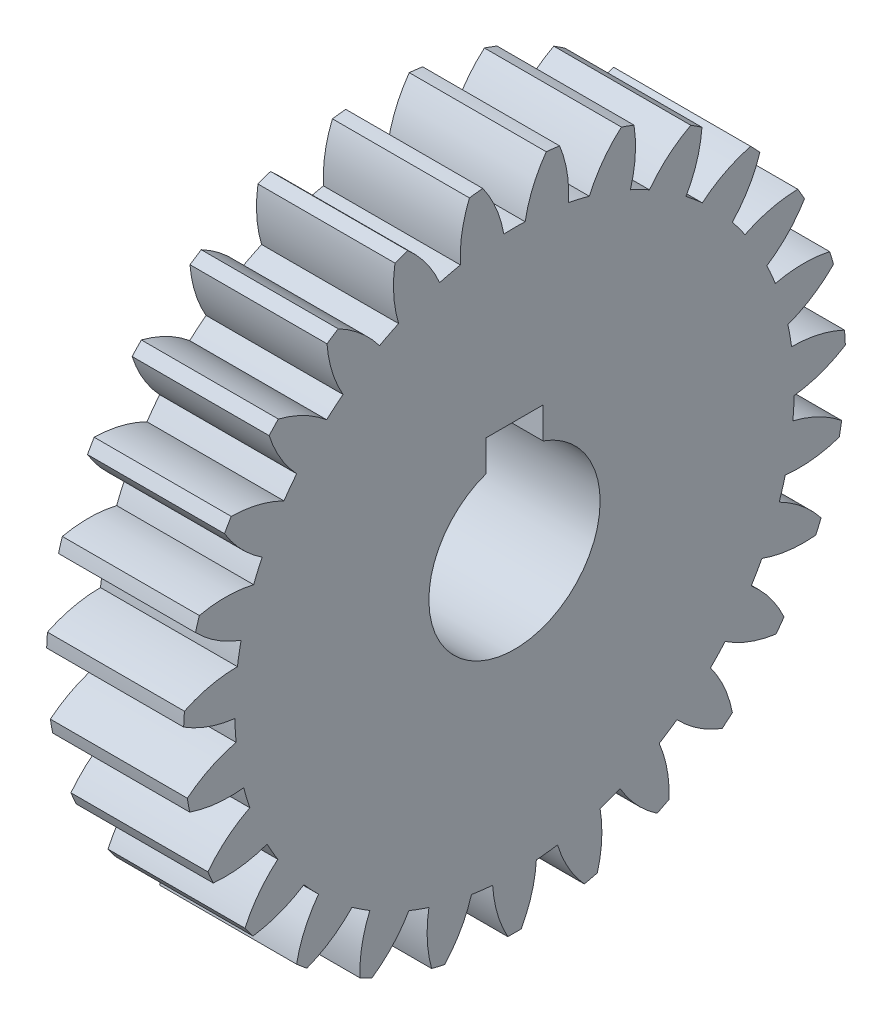
SolidWorks part; units mm, degrees
ref_plane "Plane1" through (0, 0, 0) normal (0, 0, 1) x (1, 0, 0)
ref_plane "Plane2" through (0, 0, 0) normal (0, 1, 0) x (1, 0, 0)
ref_plane "Plane3" through (0, 0, 0) normal (1, 0, 0) x (0, 0, -1)
sketch "HoldingSke" plane through (0, 0, 0) normal (0, 1, 0) x (1, 0, 0)
  line L0 (0, 0) -> (0.4455, -0.227)
  line L1 (-15, 0) -> (100, 0) construction
  line L2 (0, 0) -> (-2.1039, 2.3779)
  line L3 (0, 0) -> (-11.863, 4.5341)
  line L4 (0, 0) -> (7.6947, 3.9207)
  line L5 (0, 0) -> (-46.8476, -17.4728)
  line L6 (0, 0) -> (-9.9476, -6.7116)
  line L7 (-2.1039, 2.3779) -> (8.6586, 51.2059)
  line L8 (-76.2, 54.61) -> (-73.9, 54.61)
  line L9 (-71.009, 38.7566) -> (-53.1078, 45.2721)
  line L10 (-76.2, 71.12) -> (104.1128, 71.12)
  line L11 (0, 0) -> (-12, 0)
  line L12 (-76.2, 101.6) -> (-76.133, 101.6)
  line L13 (24.9733, 27.94) -> (52.9518, 28.4284)
  line L14 (24.9733, 27.94) -> (24.9743, 27.94)
  line L15 (24.9733, 27.94) -> (100.4006, 29.5858)
  line L16 (-63.627, -2) -> (-12.827, -2)
  circle A0 centre (0, 0) radius 7.5
  circle A1 centre (0, 0) radius 24.499
  circle A2 centre (0, 0) radius 37.5
  circle A3 centre (0, 0) radius 7.5
  dimension "MHD" = 48.998
  dimension "Hub_dia" = 75
  dimension "Bore" = 15
  dimension "MBD" = 15
  dimension "Num_teeth" = 27
  dimension "Pitch" = 0.5
  dimension "Overall_len" = 50
  dimension "Show_teeth" = 27
  dimension "Thickness" = 12
  dimension "OAL" = 50.0001
  dimension "T_dim" = 2.3
  dimension "Ap" = 20
  dimension "H" = 19.05
  dimension "Pitch_radius" = 180.3128
  dimension "Width" = 12
  dimension "Backlash" = 0.067
  dimension "Addendum_fac" = 1
  dimension "Dedendum_fac" = 1.25
  dimension "Clearance_fac" = 0.25
  dimension "Dedendum_add" = 0.001
  dimension "Module" = 2
sketch "BasProSke" plane through (0, 0, 0) normal (0, 1, 0) x (1, 0, 0)
  line L0 (-10, 0) -> (60, 0) construction
  line L1 (0, 0) -> (0, 29)
  line L2 (0, 0) -> (12, 0)
  line L3 (12, 0) -> (12, 29)
  line L4 (12, 29) -> (0, 29)
  dimension "Thickness" = 12
  dimension "Diameter" = 58
revolve "Base-Revolve" add sketch "BasProSke" angle 360 about L0
sketch "TooCutSke" plane through (0, 0, 0) normal (1, 0, 0) x (0, 0, -1)
  line L1 (0, 0) -> (0, 107) construction
  line L2 (0, 0) -> (-1.6871, 26.9472) construction
  line L3 (0, 0) -> (-6.2599, 53.5572) construction
  line L4 (-1.6871, 26.9472) -> (-3.13, 26.7786) construction
  arc A0 (0.934, 24.4812) -> (-0.934, 24.4812) centre (0, 0) ccw
  arc A1 (2.7993, 28.8901) -> (-2.7993, 28.8901) centre (0, 0) ccw
  circle A2 centre (0, 0) radius 27 construction
  circle A3 centre (0, 0) radius 25.3717 construction
  arc A4 (-0.934, 24.4812) -> (-2.7993, 28.8901) centre (-11.5657, 22.5822) ccw
  arc A5 (2.7993, 28.8901) -> (0.934, 24.4812) centre (11.5657, 22.5822) ccw
  dimension "Root_dia" = 48.998
  dimension "Overcut_dia" = 58.0508
  dimension "Pitch_dia" = 54
  dimension "Base_dia" = 50.7434
  dimension "Flank_rad" = 10.8
  dimension "Half_ang" = 6.667
  dimension "Half_CT" = 1.4527
extrude "ToothCut" cut sketch "TooCutSke" along normal through all
fillet "Breaks" [suppressed] radius 0.04
fillet "RootFillets" [suppressed] radius 0.501
pattern_circular "TeethCuts" count 27 every 13.333 about axis through (-10, 0, 0) along (1, 0, 0) of "ToothCut", "RootFillets", "Breaks"
sketch "HubNeaOneSke" plane through (0, 0, 0) normal (-1, 0, 0) x (0, 0, 1)
  circle A0 centre (0, 0) radius 24.499
  dimension "Diameter" = 48.998
extrude "HubNearOne" [suppressed] add sketch "HubNeaOneSke" along normal blind 38.0001
sketch "HubNeaBotSke" plane through (0, 0, 0) normal (-1, 0, 0) x (0, 0, 1)
  circle A0 centre (0, 0) radius 24.499
  dimension "Diameter" = 48.998
extrude "HubNearBoth" [suppressed] add sketch "HubNeaBotSke" along normal blind 19
ref_plane "FarPln" through (12, 0, 0) normal (1, 0, 0) x (0, 0, -1)
sketch "HubFarSke" plane through (12, 0, 0) normal (1, 0, 0) x (0, 0, -1)
  circle A0 centre (0, 0) radius 24.499
  dimension "Diameter" = 48.998
extrude "HubFar" [suppressed] add sketch "HubFarSke" along normal blind 19
sketch "BorSke" plane through (0, 0, 0) normal (1, 0, 0) x (0, 0, -1)
  circle A0 centre (0, 0) radius 7.5
  dimension "Diameter" = 15
extrude "Bore" cut sketch "BorSke" along normal mid plane 100.0001
sketch "KeySke" plane through (0, 0, 0) normal (1, 0, 0) x (0, 0, -1)
  line L0 (-2.5, 0) -> (-2.5, 9.8)
  line L1 (-2.5, 9.8) -> (2.5, 9.8)
  line L2 (2.5, 9.8) -> (2.5, 0)
  line L3 (0, 0) -> (0, 34) construction
  line L4 (-2.5, 0) -> (2.5, 0)
  dimension "Offset" = 9.8
  dimension "Width" = 5
extrude "Keyway" cut sketch "KeySke" along normal mid plane 100.0001
pattern_circular "Keyway2" [suppressed] count 2 every 90 about axis through (-10, 0, 0) along (1, 0, 0)
equation "' \"Module@HoldingSke\" = 6.35"
equation "' \"Num_teeth@HoldingSke\" = 12"
equation "' \"Ap@HoldingSke\" =  20"
equation "' \"Ap@HoldingSke\" = 20"
equation "' \"Width@HoldingSke\" = 0.5 * 25.4"
equation "' \"Hub_dia@HoldingSke\"= 1 * 25.4"
equation "' \"Hub_dia@HoldingSke\" = 1 * 25.4"
equation "' \"Overall_len@HoldingSke\" = 1.0 * 25.4"
equation "' \"Bore@HoldingSke\" = 0.75 * 25.4"
equation "' \"T_dim@HoldingSke\" = 0.1 * 25.4"
equation "' \"Width@KeySke\" = 0.25 * 25.4"
equation "' \"Show_teeth@HoldingSke\" = 13"
equation "' \"Backlash@HoldingSke\" = 0.009 * 25.4"
equation "' \"Addendum_fac@HoldingSke\" = 1.0"
equation "' \"Dedendum_fac@HoldingSke\" = 1.25"
equation "' \"Dedendum_add@HoldingSke\" = 0.00005 * 25.4"
equation "' \"Clearance_fac@HoldingSke\" = 0.25"
equation "\"Pitch@HoldingSke\" = 1 / \"Module@HoldingSke\""
equation "\"Overcut_dia@TooCutSke\" = (\"Num_teeth@HoldingSke\" + 2 * \"Addendum_fac@HoldingSke\") / \"Pitch@HoldingSke\" + 0.002 * 25.4"
equation "\"Pitch_dia@TooCutSke\" = \"Num_teeth@HoldingSke\" / \"Pitch@HoldingSke\""
equation "\"Base_dia@TooCutSke\" = \"Num_teeth@HoldingSke\" / \"Pitch@HoldingSke\" * cos((\"Ap@HoldingSke\"  * 3.14159265 / 180))"
equation "\"Root_dia@TooCutSke\" = (\"Num_teeth@HoldingSke\" + 2) / \"Pitch@HoldingSke\" - 2 * (\"Addendum_fac@HoldingSke\" + \"Dedendum_fac@HoldingSke\") / \"Pitch@HoldingSke\" - \"Dedendum_add@HoldingSke\" * 2"
equation "\"Half_ang@TooCutSke\" = 180 / \"Num_teeth@HoldingSke\""
equation "\"Half_CT@TooCutSke\" = \"Num_teeth@HoldingSke\" / \"Pitch@HoldingSke\" * sin((3.14159265 / 2 / \"Num_teeth@HoldingSke\")) / 2 - 7 * \"Backlash@HoldingSke\" / 4"
equation "\"Flank_rad@TooCutSke\" = \"Num_teeth@HoldingSke\" / \"Pitch@HoldingSke\" / 5"
equation "\"Radius@RootFillets\" = \"Clearance_fac@HoldingSke\" / \"Pitch@HoldingSke\" + \"Dedendum_add@HoldingSke\""
equation "\"Break_rad@Breaks\" = 0.02 / \"Pitch@HoldingSke\""
equation "\"Thickness@HoldingSke\" = \"Width@HoldingSke\""
equation "\"OAL@HoldingSke\" = \"Thickness@HoldingSke\""
equation "\"MHD@HoldingSke\" = (\"Num_teeth@HoldingSke\" + 2) / \"Pitch@HoldingSke\" - 2 * (\"Addendum_fac@HoldingSke\" + \"Dedendum_fac@HoldingSke\")  / \"Pitch@HoldingSke\" - \"Dedendum_add@HoldingSke\" * 2"
equation "\"MBD@HoldingSke\" = (\"Num_teeth@HoldingSke\" + 2) / \"Pitch@HoldingSke\" - 2 * (\"Addendum_fac@HoldingSke\" + \"Dedendum_fac@HoldingSke\")  / \"Pitch@HoldingSke\" - \"Dedendum_add@HoldingSke\" * 2 - 0.002 * 25.4"
equation "\"MHD@HoldingSke\" = ((sgn( \"MHD@HoldingSke\" - \"Hub_dia@HoldingSke\" )-1)*( \"MHD@HoldingSke\" - \"Hub_dia@HoldingSke\" ))/-2+ \"Hub_dia@HoldingSke\""
equation "\"MBD@HoldingSke\" = ((sgn( \"MBD@HoldingSke\" - \"Bore@HoldingSke\" )-1)*( \"MBD@HoldingSke\" - \"Bore@HoldingSke\" ))/-2+ \"Bore@HoldingSke\""
equation "\"OAL@HoldingSke\" = ((sgn( \"OAL@HoldingSke\" - \"Overall_len@HoldingSke\" )+1)*( \"OAL@HoldingSke\" - \"Overall_len@HoldingSke\" ))/2 + \"Overall_len@HoldingSke\" + 0.000002 * 25.4"
equation "\"Num_teeth@TeethCuts\" = int( \"Show_teeth@HoldingSke\" ) + 1"
equation "\"Num_teeth@TeethCuts\" = ((sgn( \"Num_teeth@TeethCuts\" - \"Num_teeth@HoldingSke\" )-1)*( \"Num_teeth@TeethCuts\" - \"Num_teeth@HoldingSke\" ))/-2+ \"Num_teeth@HoldingSke\""
equation "\"Num_teeth@TeethCuts\" = ((sgn( \"Num_teeth@TeethCuts\" - 2.0)+1)*( \"Num_teeth@TeethCuts\" - 2.0))/2 +2.0"
equation "\"Angle@TeethCuts\" = 360.0 / \"Num_teeth@HoldingSke\""
equation "\"Diameter@BasProSke\" = (\"Num_teeth@HoldingSke\" + 2 * \"Addendum_fac@HoldingSke\") / \"Pitch@HoldingSke\""
equation "\"Thickness@BasProSke\"  = \"Thickness@HoldingSke\""
equation "' \"Fillet_rad@BasProSke\" =  \"Thickness@HoldingSke\" * 0.05"
equation "' \"Fillet_rad@BasProSke\" = \"Thickness@HoldingSke\" * 0.05"
equation "\"MHD@HoldingSke\" = ((sgn( \"MHD@HoldingSke\" - \"Root_dia@TooCutSke\" )-1)*( \"MHD@HoldingSke\" - \"Root_dia@TooCutSke\" ))/-2+ \"Root_dia@TooCutSke\""
equation "\"Diameter@HubNeaOneSke\" = \"MHD@HoldingSke\""
equation "\"Length@HubNearOne\" = \"OAL@HoldingSke\" - \"Thickness@BasProSke\""
equation "\"Diameter@HubNeaBotSke\" = \"MHD@HoldingSke\""
equation "\"Length@HubNearBoth\" = ( \"OAL@HoldingSke\" - \"Thickness@BasProSke\" ) / 2.0"
equation "\"Thickness@FarPln\" = \"Thickness@BasProSke\""
equation "\"Diameter@HubFarSke\" = \"MHD@HoldingSke\""
equation "\"Length@HubFar\" = ( \"OAL@HoldingSke\" - \"Thickness@BasProSke\" ) / 2.0"
equation "\"Diameter@BorSke\" = \"MBD@HoldingSke\""
equation "\"D1@Bore\" = \"OAL@HoldingSke\" * 2.0"
equation "\"D1@Keyway\" = \"OAL@HoldingSke\" * 2.0"
equation "\"Offset@KeySke\" = \"T_dim@HoldingSke\" + \"MBD@HoldingSke\" / 2.0"
